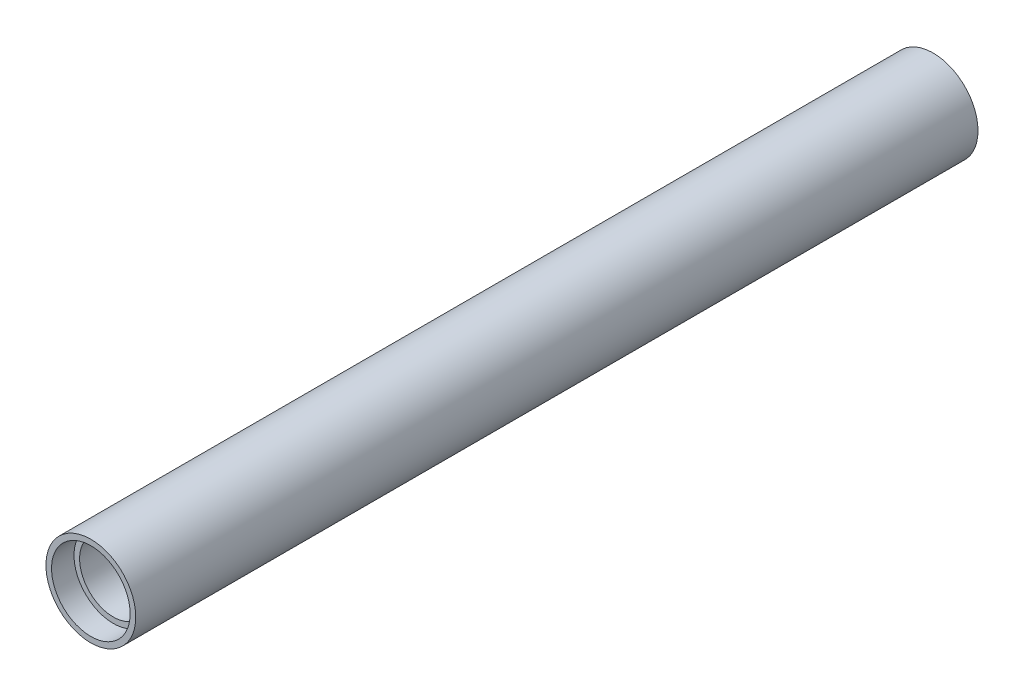
SolidWorks part; units mm, degrees
ref_plane "前视基准面" through (0, 0, 0) normal (0, 0, 1) x (1, 0, 0)
ref_plane "上视基准面" through (0, 0, 0) normal (0, 1, 0) x (1, 0, 0)
ref_plane "右视基准面" through (0, 0, 0) normal (1, 0, 0) x (0, 0, -1)
sketch "草图1" plane through (0, 0, 0) normal (0, 0, 1) x (1, 0, 0)
  circle A0 centre (0, 0) radius 21
  dimension "D1" = 42
extrude "拉伸-薄壁1" add sketch "草图1" along normal mid plane 450 thin
sketch "草图2" plane through (0, 0, 225) normal (0, 0, 1) x (1, 0, 0)
  circle A0 centre (0, 0) radius 21
  dimension "D1" = 42
extrude "拉伸-薄壁2" add sketch "草图2" against normal up to surface (213 mm away) from offset 12 thin up to plane "前视基准面" thin type one direction reverse wall 3 offset against normal yes
mirror "镜向1" about plane through (0, 0, 0) normal (0, 0, 1) of "拉伸-薄壁2"
